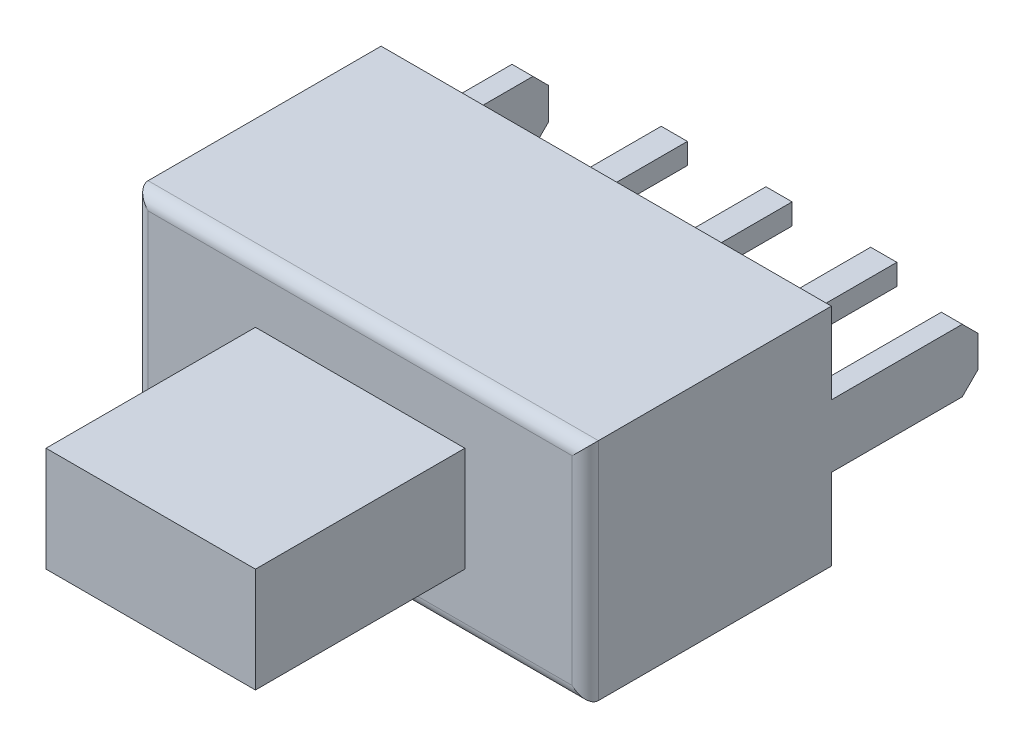
SolidWorks part; units mm, degrees
ref_plane "Front Plane" through (0, 0, 0) normal (0, 0, 1) x (1, 0, 0)
ref_plane "Top Plane" through (0, 0, 0) normal (0, 1, 0) x (1, 0, 0)
ref_plane "Right Plane" through (0, 0, 0) normal (1, 0, 0) x (0, 0, -1)
sketch "Sketch1" plane through (0, 0, 0) normal (0, 0, 1) x (1, 0, 0)
  line L1 (-4.3, -2.15) -> (4.3, -2.15)
  line L2 (-4.3, -2.15) -> (-4.3, 2.15)
  line L3 (-4.3, 2.15) -> (4.3, 2.15)
  line L4 (4.3, -2.15) -> (4.3, 2.15)
  line L5 (-4.3, -2.15) -> (4.3, 2.15) construction
  line L6 (-4.3, 2.15) -> (4.3, -2.15) construction
  point P0 (0, 0)
  dimension "D1" = 4.3
  dimension "D2" = 8.6
extrude "Boss-Extrude1" add sketch "Sketch1" along normal blind 4.7
sketch "Sketch2" plane through (0, 0, 4.7) normal (0, 0, 1) x (1, 0, 0)
  line L1 (-2, -1) -> (2, -1)
  line L2 (-2, -1) -> (-2, 1)
  line L3 (-2, 1) -> (2, 1)
  line L4 (2, -1) -> (2, 1)
  line L5 (-2, -1) -> (2, 1) construction
  line L6 (-2, 1) -> (2, -1) construction
  point P0 (0, 0)
  dimension "D1" = 4
  dimension "D2" = 2
extrude "Boss-Extrude2" add sketch "Sketch2" along normal blind 4
sketch "Sketch3" plane through (0, 0, 0) normal (0, 0, -1) x (-1, 0, 0)
  line L0 (4.3, 2.15) -> (4.3, -2.15) construction
  line L1 (-4.3, 0.6) -> (4.3, 0.6)
  line L2 (-4.3, 0.6) -> (-4.3, -0.6)
  line L3 (-4.3, -0.6) -> (4.3, -0.6)
  line L4 (4.3, 0.6) -> (4.3, -0.6)
  line L5 (-4.3, 0.6) -> (4.3, -0.6) construction
  line L6 (-4.3, -0.6) -> (4.3, 0.6) construction
  line L8 (-3.9, 0.6) -> (3.9, 0.6)
  line L9 (-3.9, 0.6) -> (-3.9, -0.6)
  line L10 (-3.9, -0.6) -> (3.9, -0.6)
  line L11 (3.9, 0.6) -> (3.9, -0.6)
  line L12 (-3.9, 0.6) -> (3.9, -0.6) construction
  line L13 (-3.9, -0.6) -> (3.9, 0.6) construction
  point P0 (0, 0)
  point P8 (0, 0)
  line M4 (-4.3, 2.15) -> (-4.3, -2.15)
  line M6 (4.3, -2.15) -> (4.3, 2.15)
  dimension "D1" = 1.2
  dimension "D2" = 0.4
extrude "Boss-Extrude3" add sketch "Sketch3" along normal blind 2.8 contours L9 L1 L3 M4 | L1 L11 L3 M6
sketch "Sketch4" plane through (0, 0, 0) normal (0, 0, -1) x (-1, 0, 0)
  line L1 (-2.25, 0.2) -> (2.25, 0.2)
  line L2 (-2.25, 0.2) -> (-2.25, -0.2)
  line L3 (-2.25, -0.2) -> (2.25, -0.2)
  line L4 (2.25, 0.2) -> (2.25, -0.2)
  line L5 (-2.25, 0.2) -> (2.25, -0.2) construction
  line L6 (-2.25, -0.2) -> (2.25, 0.2) construction
  line L7 (0.25, 0.2) -> (1.75, 0.2)
  line L8 (0.25, 0.2) -> (0.25, -0.2)
  line L9 (0.25, -0.2) -> (1.75, -0.2)
  line L10 (1.75, 0.2) -> (1.75, -0.2)
  line L11 (0.25, 0.2) -> (1.75, -0.2) construction
  line L12 (0.25, -0.2) -> (1.75, 0.2) construction
  line L13 (-0.25, 0.2) -> (-1.75, 0.2)
  line L14 (-0.25, 0.2) -> (-0.25, -0.2)
  line L15 (-0.25, -0.2) -> (-1.75, -0.2)
  line L16 (-1.75, 0.2) -> (-1.75, -0.2)
  line L17 (-0.25, 0.2) -> (-1.75, -0.2) construction
  line L18 (-0.25, -0.2) -> (-1.75, 0.2) construction
  point P0 (0, 0)
  point P6 (1, 0)
  point P11 (-1, 0)
  dimension "D1" = 0.4
  dimension "D2" = 4.5
  dimension "D3" = 0.25
  dimension "D4" = 0.5
  dimension "D5" = 0.5
  dimension "D6" = 0.25
extrude "Boss-Extrude4" add sketch "Sketch4" along normal blind 3.3 contours L1 L10 L3 L4 | L1 L14 L3 L8 | L16 L1 L2 L3
chamfer "Chamfer1" distance 0.3 angle 45 4 edges at (4.1, -0.6, -2.8) (-4.1, -0.6, -2.8) (4.1, 0.6, -2.8) (-4.1, 0.6, -2.8)
fillet "Fillet1" radius 0.25 4 edges at (4.3, 0, 4.7) (-4.3, 0, 4.7) (0, -2.15, 4.7) (0, 2.15, 4.7)
